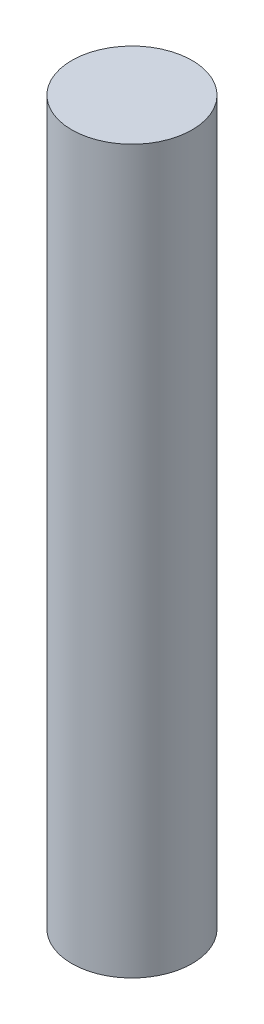
SolidWorks part; units mm, degrees
ref_plane "정면" through (0, 0, 0) normal (0, 0, 1) x (1, 0, 0)
ref_plane "윗면" through (0, 0, 0) normal (0, 1, 0) x (1, 0, 0)
ref_plane "우측면" through (0, 0, 0) normal (1, 0, 0) x (0, 0, -1)
sketch "스케치1" plane through (0, 0, 0) normal (0, 1, 0) x (1, 0, 0)
  circle A0 centre (0, 0) radius 2.5
extrude "보스-돌출1" add sketch "스케치1" along normal blind 30 contours A0
